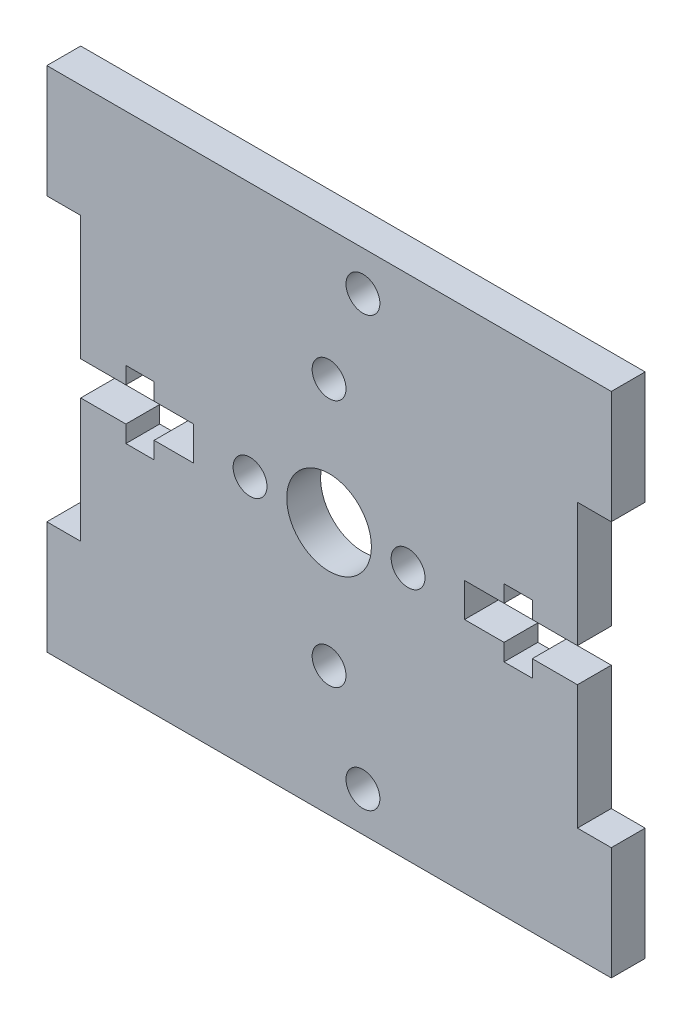
SolidWorks part; units mm, degrees
ref_plane "Plan de face" through (0, 0, 0) normal (0, 0, 1) x (1, 0, 0)
ref_plane "Plan de dessus" through (0, 0, 0) normal (0, 1, 0) x (1, 0, 0)
ref_plane "Plan de droite" through (0, 0, 0) normal (1, 0, 0) x (0, 0, -1)
sketch "Esquisse11" plane through (0, 0, 0) normal (0, 0, 1) x (1, 0, 0)
  line L0 (-66.0081, -86.4966) -> (-66.0081, -75.4966)
  line L1 (-69.0081, -65.4966) -> (-19.0081, -65.4966)
  line L2 (-69.0081, -65.4966) -> (-69.0081, -75.4966)
  line L3 (-69.0081, -110.4966) -> (-19.0081, -110.4966)
  line L4 (-19.0081, -65.4966) -> (-19.0081, -75.4966)
  line L5 (-56.0081, -89.4966) -> (-59.5081, -89.4966)
  line L6 (-56.0081, -89.4966) -> (-56.0081, -86.4966)
  line L7 (-56.0081, -86.4966) -> (-59.5081, -86.4966)
  line L8 (-62.0081, -86.4966) -> (-62.0081, -84.9966)
  line L9 (-32.0081, -89.4966) -> (-28.5081, -89.4966)
  line L10 (-32.0081, -89.4966) -> (-32.0081, -86.4966)
  line L11 (-32.0081, -86.4966) -> (-28.5081, -86.4966)
  line L13 (-69.0081, -100.4966) -> (-66.0081, -100.4966)
  line L14 (-19.0081, -100.4966) -> (-19.0081, -110.4966)
  line L15 (-69.0081, -75.4966) -> (-66.0081, -75.4966)
  line L16 (-66.0081, -100.4966) -> (-66.0081, -89.4966)
  line L17 (-19.0081, -100.4966) -> (-22.0081, -100.4966)
  line L19 (-19.0081, -75.4966) -> (-22.0081, -75.4966)
  line L20 (-22.0081, -100.4966) -> (-22.0081, -89.4966)
  line L21 (-69.0081, -100.4966) -> (-69.0081, -110.4966)
  line L22 (-22.0081, -86.4966) -> (-22.0081, -75.4966)
  line L24 (-28.5081, -90.9966) -> (-26.0081, -90.9966)
  line L25 (-28.5081, -90.9966) -> (-28.5081, -89.4966)
  line L26 (-28.5081, -84.9966) -> (-26.0081, -84.9966)
  line L27 (-26.0081, -90.9966) -> (-26.0081, -89.4966)
  line L28 (-59.5081, -90.9966) -> (-62.0081, -90.9966)
  line L29 (-59.5081, -90.9966) -> (-59.5081, -89.4966)
  line L30 (-59.5081, -84.9966) -> (-62.0081, -84.9966)
  line L31 (-62.0081, -90.9966) -> (-62.0081, -89.4966)
  line L32 (-59.5081, -86.4966) -> (-59.5081, -84.9966)
  line L33 (-62.0081, -86.4966) -> (-66.0081, -86.4966)
  line L34 (-62.0081, -89.4966) -> (-66.0081, -89.4966)
  line L35 (-28.5081, -86.4966) -> (-28.5081, -84.9966)
  line L36 (-26.0081, -86.4966) -> (-26.0081, -84.9966)
  line L37 (-26.0081, -86.4966) -> (-22.0081, -86.4966)
  line L38 (-26.0081, -89.4966) -> (-22.0081, -89.4966)
  circle A0 centre (-44.0081, -88.0456) radius 3.75
  circle A1 centre (-37.0081, -88.0456) radius 1.5
  circle A2 centre (-51.0081, -88.0456) radius 1.5
  circle A3 centre (-44.0081, -77.0456) radius 1.5
  circle A4 centre (-44.0081, -99.0456) radius 1.5
  circle A5 centre (-41.0081, -68.9966) radius 1.5
  circle A6 centre (-41.0081, -106.9966) radius 1.5
  dimension "D5" = 25
  dimension "D6" = 7.5
  dimension "D7" = 3
  dimension "D8" = 3
  dimension "D9" = 7
  dimension "D10" = 7
  dimension "D15" = 3
  dimension "D16" = 3
  dimension "D17" = 11
  dimension "D18" = 11
  dimension "D19" = 3
  dimension "D21" = 22
  dimension "D22" = 3
  dimension "D23" = 3.5
  dimension "D24" = 22
  dimension "D20" = 38
  dimension "D1" = 45
  dimension "D2" = 50
  dimension "D3" = 13
  dimension "D4" = 13
  dimension "D11" = 3
  dimension "D12" = 3
  dimension "D13" = 21
  dimension "D14" = 21
  dimension "D25" = 3
  dimension "D26" = 3
  dimension "D27" = 10
  dimension "D28" = 10
  dimension "D29" = 10
  dimension "D30" = 10
  dimension "D31" = 1.5
  dimension "D32" = 1.5
  dimension "D33" = 1.5
  dimension "D34" = 1.5
  dimension "D35" = 2.5
  dimension "D36" = 2.5
  dimension "D37" = 4
  dimension "D38" = 4
extrude "Boss.-Extru.11" add sketch "Esquisse11" along normal blind 3 separate body
